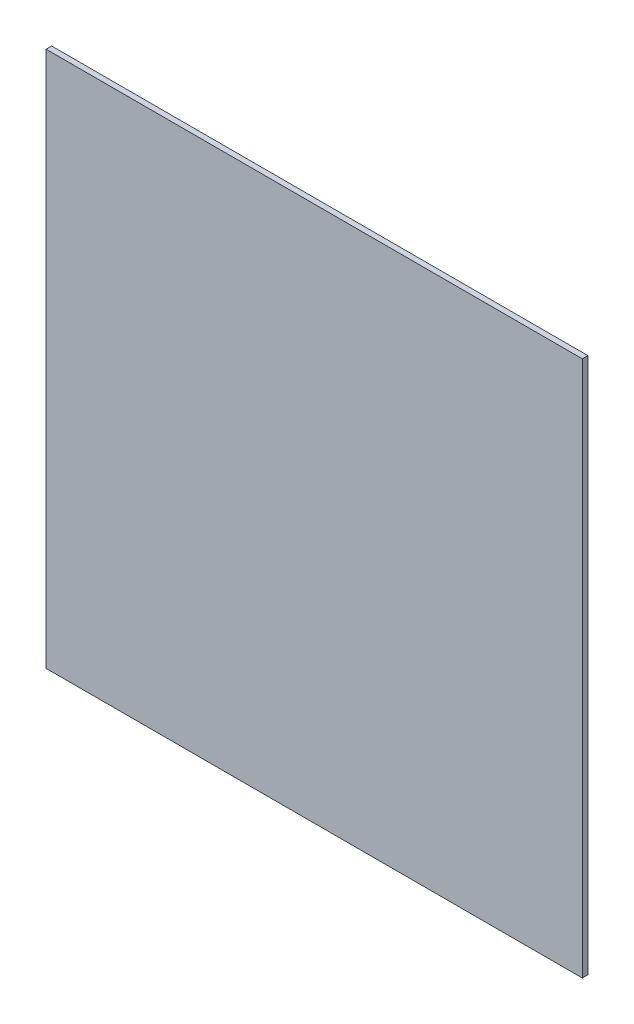
SolidWorks part; units mm, degrees
material "Custom Plastic"
ref_plane "X-Y Datum" through (0, 0, 0) normal (0, 0, 1) x (1, 0, 0)
ref_plane "X-Z Datum" through (0, 0, 0) normal (0, 1, 0) x (1, 0, 0)
ref_plane "Y-Z Datum" through (0, 0, 0) normal (1, 0, 0) x (0, 0, -1)
sketch "Sketch2" plane through (0, 0, 0) normal (0, 0, 1) x (1, 0, 0)
  line L1 (-304.8, 304.8) -> (304.8, 304.8)
  line L2 (-304.8, 304.8) -> (-304.8, -304.8)
  line L3 (-304.8, -304.8) -> (304.8, -304.8)
  line L4 (304.8, 304.8) -> (304.8, -304.8)
  line L5 (-304.8, 304.8) -> (304.8, -304.8) construction
  line L6 (-304.8, -304.8) -> (304.8, 304.8) construction
  point P0 (0, 0)
  dimension "D1" = 609.6
  dimension "D2" = 609.6
extrude "Boss-Extrude1" add sketch "Sketch2" along normal blind 6.35
